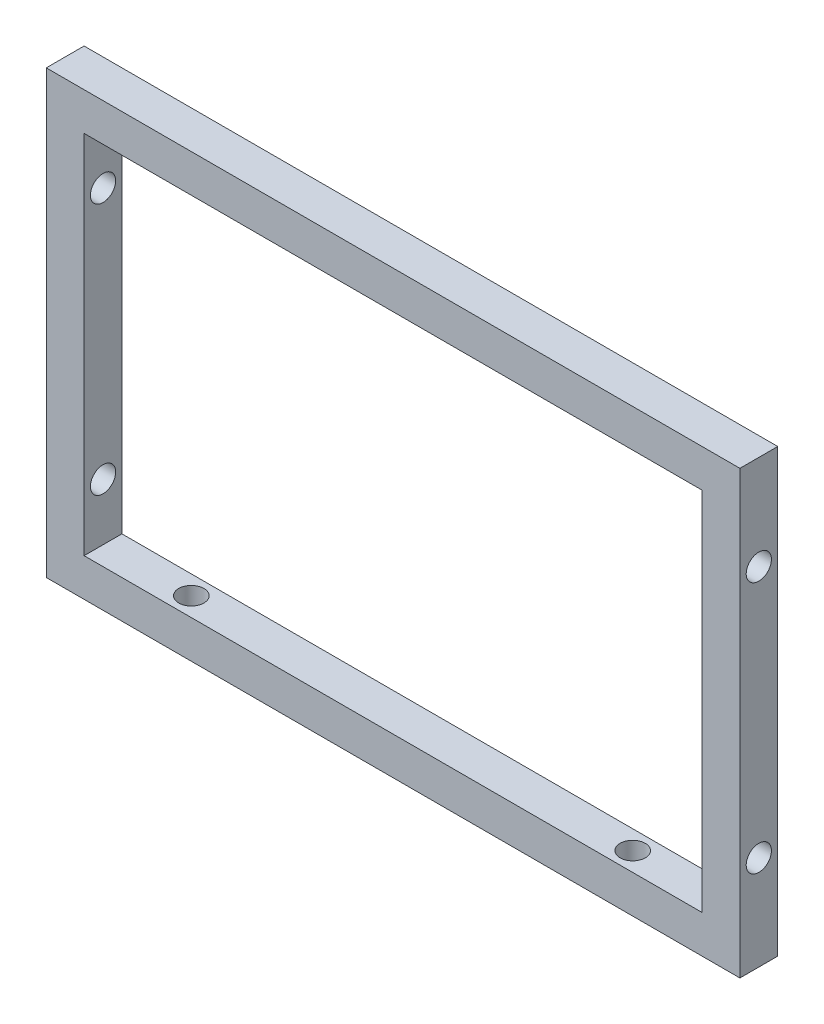
SolidWorks part; units mm, degrees
ref_plane "前视基准面" through (0, 0, 0) normal (0, 0, 1) x (1, 0, 0)
ref_plane "上视基准面" through (0, 0, 0) normal (0, 1, 0) x (1, 0, 0)
ref_plane "右视基准面" through (0, 0, 0) normal (1, 0, 0) x (0, 0, -1)
sketch "草图1" plane through (0, 0, 0) normal (0, 0, 1) x (1, 0, 0)
  line L1 (-55, -35) -> (55, -35)
  line L2 (-55, -35) -> (-55, 35)
  line L3 (-55, 35) -> (55, 35)
  line L4 (55, -35) -> (55, 35)
  line L5 (-55, -35) -> (55, 35) construction
  line L6 (-55, 35) -> (55, -35) construction
  line L7 (-49, -29) -> (49, -29)
  line L8 (-49, -29) -> (-49, 29)
  line L9 (-49, 29) -> (49, 29)
  line L10 (49, -29) -> (49, 29)
  line L11 (-49, -29) -> (49, 29) construction
  line L12 (-49, 29) -> (49, -29) construction
  point P0 (0, 0)
  point P6 (0, 0)
  dimension "D1" = 70
  dimension "D2" = 58
  dimension "D3" = 110
  dimension "D4" = 98
extrude "凸台-拉伸1" add sketch "草图1" along normal blind 6
sketch "草图3" plane through (0, -35, 0) normal (0, -1, 0) x (1, 0, 0)
  line L0 (-55, 0) -> (55, 0) construction
  circle A0 centre (-35, 3) radius 2
  circle A1 centre (35, 3) radius 2
  dimension "D1" = 4
  dimension "D2" = 4
  dimension "D3" = 3
  dimension "D4" = 3
  dimension "D5" = 35
  dimension "D6" = 35
extrude "切除-拉伸2" cut sketch "草图3" against normal blind 6
sketch "草图4" plane through (55, 0, 0) normal (1, 0, 0) x (0, 0, -1)
  line L0 (-6, -35) -> (-6, 35) construction
  circle A0 centre (-3, 20) radius 2
  circle A1 centre (-3, -20) radius 2
  dimension "D1" = 4
  dimension "D2" = 4
  dimension "D3" = 3
  dimension "D4" = 3
  dimension "D5" = 20
  dimension "D6" = 20
extrude "切除-拉伸3" cut sketch "草图4" against normal blind 110
